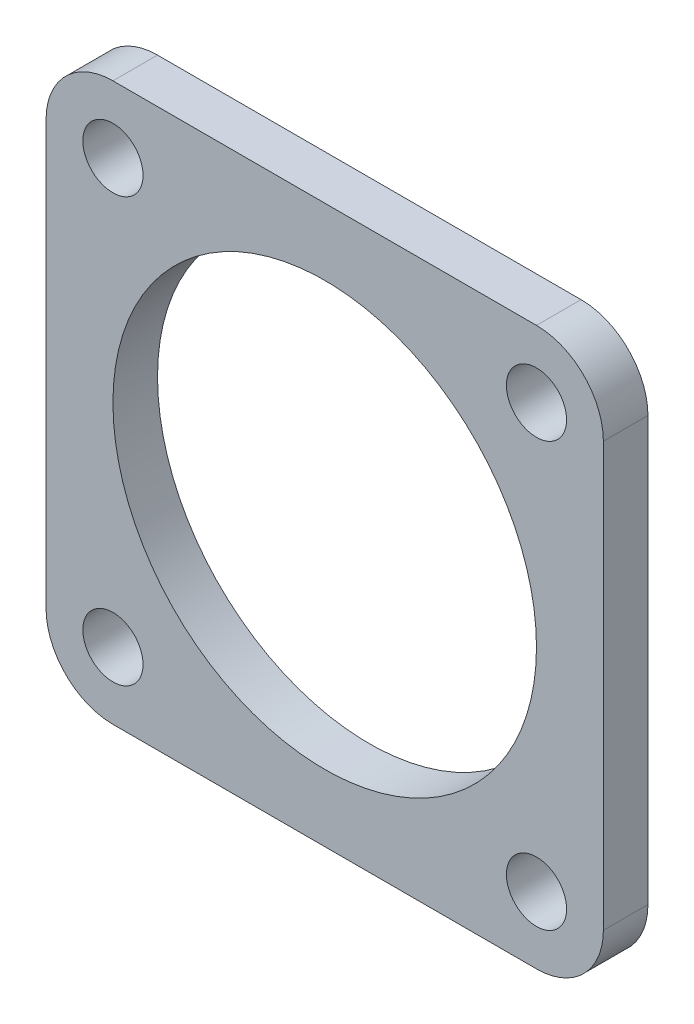
SolidWorks part; units mm, degrees
ref_plane "Front Plane" through (0, 0, 0) normal (0, 0, 1) x (1, 0, 0)
ref_plane "Top Plane" through (0, 0, 0) normal (0, 1, 0) x (1, 0, 0)
ref_plane "Right Plane" through (0, 0, 0) normal (1, 0, 0) x (0, 0, -1)
sketch "Sketch1" plane through (0, 0, 0) normal (0, 0, 1) x (1, 0, 0)
  line L1 (-12.5, -12.5) -> (12.5, -12.5)
  line L2 (-12.5, -12.5) -> (-12.5, 12.5)
  line L3 (-12.5, 12.5) -> (12.5, 12.5)
  line L4 (12.5, -12.5) -> (12.5, 12.5)
  line L5 (-12.5, -12.5) -> (12.5, 12.5) construction
  line L6 (-12.5, 12.5) -> (12.5, -12.5) construction
  circle A0 centre (-9.5, 9.5) radius 1.35
  circle A1 centre (9.5, 9.5) radius 1.35
  circle A2 centre (9.5, -9.5) radius 1.35
  circle A3 centre (-9.5, -9.5) radius 1.35
  circle A4 centre (0, 0) radius 9.5
  point P0 (0, 0)
  point P17 (0, 0)
  dimension "D2" = 2.7
  dimension "D5" = 19
  dimension "D1" = 25
  dimension "D4" = 19
  dimension "D3" = 4
extrude "Boss-Extrude1" add sketch "Sketch1" along normal mid plane 2
fillet "Fillet1" radius 3 4 edges at (12.5, -12.5, 0) (-12.5, -12.5, 0) (12.5, 12.5, 0) (-12.5, 12.5, 0)
